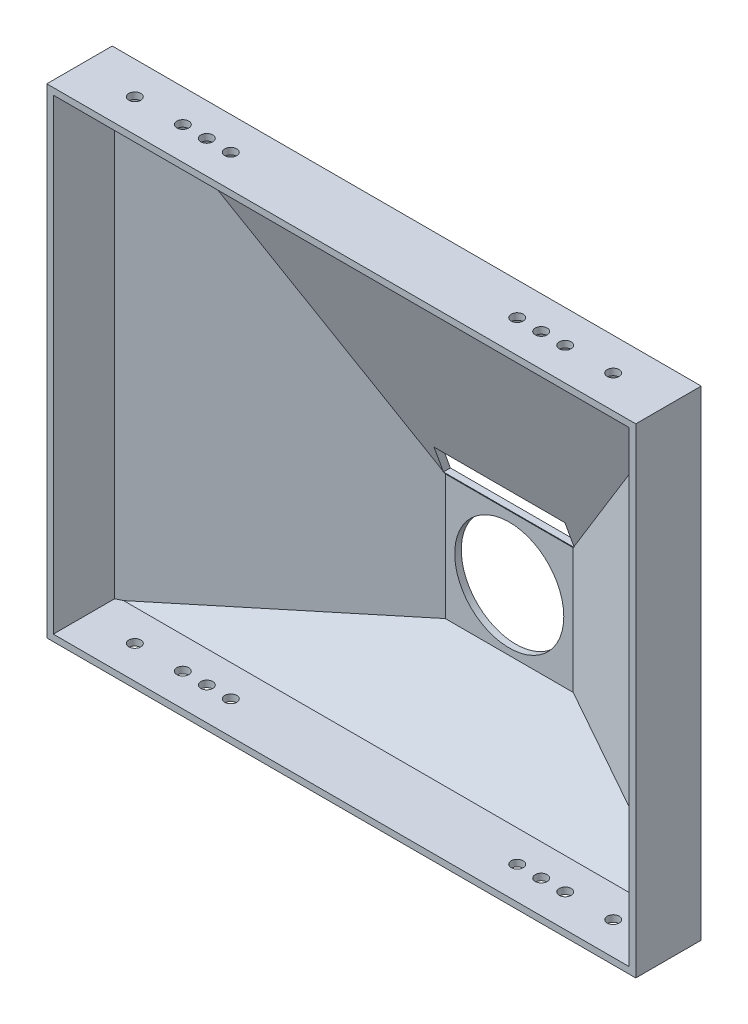
SolidWorks part; units mm, degrees
ref_plane "前视基准面" through (0, 0, 0) normal (0, 0, 1) x (1, 0, 0)
ref_plane "上视基准面" through (0, 0, 0) normal (0, 1, 0) x (1, 0, 0)
ref_plane "右视基准面" through (0, 0, 0) normal (1, 0, 0) x (0, 0, -1)
sketch "草图1" plane through (0, 0, 0) normal (0, 0, 1) x (1, 0, 0)
  line L1 (-30, 30) -> (30, 30)
  line L2 (-30, 30) -> (-30, -30)
  line L3 (-30, -30) -> (30, -30)
  line L4 (30, 30) -> (30, -30)
  line L5 (-30, 30) -> (30, -30) construction
  line L6 (-30, -30) -> (30, 30) construction
  point P0 (0, 0)
  dimension "D1" = 60
ref_plane "基准面1" through (0, 0, 50) normal (0, 0, 1) x (1, 0, 0)
sketch "草图2" plane through (0, 0, 50) normal (0, 0, 1) x (1, 0, 0)
  line L1 (-135, 170) -> (135, 170)
  line L2 (-135, 170) -> (-135, -50)
  line L3 (-135, -50) -> (135, -50)
  line L4 (135, 170) -> (135, -50)
  line L5 (-135, 170) -> (135, -50) construction
  line L6 (-135, -50) -> (135, 170) construction
  point P0 (0, 60)
  dimension "D1" = 270
  dimension "D2" = 220
  dimension "D3" = 60
loft "放样2" add profiles "草图2", "草图1"
ref_plane "基准面2" through (0, 0, 80) normal (0, 0, 1) x (1, 0, 0)
sketch "草图5" plane through (0, 0, 80) normal (0, 0, 1) x (1, 0, 0)
  line L4 (135, -50) -> (135, 170)
  line L5 (135, 170) -> (-135, 170)
  line L6 (-135, 170) -> (-135, -50)
  line L7 (-135, -50) -> (135, -50)
  line L8 (135, -50) -> (135, 170)
  line L9 (135, 170) -> (-135, 170)
  line L10 (-135, 170) -> (-135, -50)
  line L11 (-135, -50) -> (135, -50)
  dimension "D1" = 0
extrude "凸台-拉伸1" add sketch "草图5" against normal up to next
shell "抽壳1" thickness 3
sketch "草图3" plane through (0, 0, 3) normal (0, 0, 1) x (1, 0, 0)
  circle A0 centre (0, 0) radius 25
  dimension "D1" = 50
extrude "切除-拉伸1" cut sketch "草图3" against normal blind 10
sketch "草图4" plane through (0, 0, 0) normal (0, 0, -1) x (-1, 0, 0)
  line L0 (0, 0) -> (0, 114.7443) construction
  line L1 (30, 42) -> (-30, 42)
  line L2 (-30, 42) -> (-30, 30)
  line L3 (-30, 30) -> (30, 30)
  line L4 (30, 42) -> (30, 30)
  point P8 (0, 30)
  point P9 (0, 42)
  dimension "D1" = 30
  dimension "D2" = 12
  dimension "D3" = 30
extrude "切除-拉伸2" cut sketch "草图4" against normal blind 30
sketch "草图6" plane through (0, -50, 0) normal (0, -1, 0) x (1, 0, 0)
  line L0 (135, 50) -> (135, 80) construction
  circle A0 centre (65.65, 65) radius 2.75
  circle A1 centre (76.65, 65) radius 2.75
  circle A2 centre (87.65, 65) radius 2.75
  circle A3 centre (109.65, 65) radius 2.75
  point P4 (135, 65)
  point P11 (0, 0)
  dimension "D3" = 5.5
  dimension "D1" = 69.35
  dimension "D4" = 22
  dimension "D2" = 3
extrude "切除-拉伸3" cut sketch "草图6" against normal blind 10
ref_plane "基准面3" through (0, 60, 0) normal (0, -1, 0) x (-1, 0, 0)
mirror "镜向1" about plane through (0, 60, 0) normal (0, -1, 0) of "切除-拉伸3"
mirror "镜向2" about plane through (0, 0, 0) normal (1, 0, 0) of "镜向1", "切除-拉伸3"
